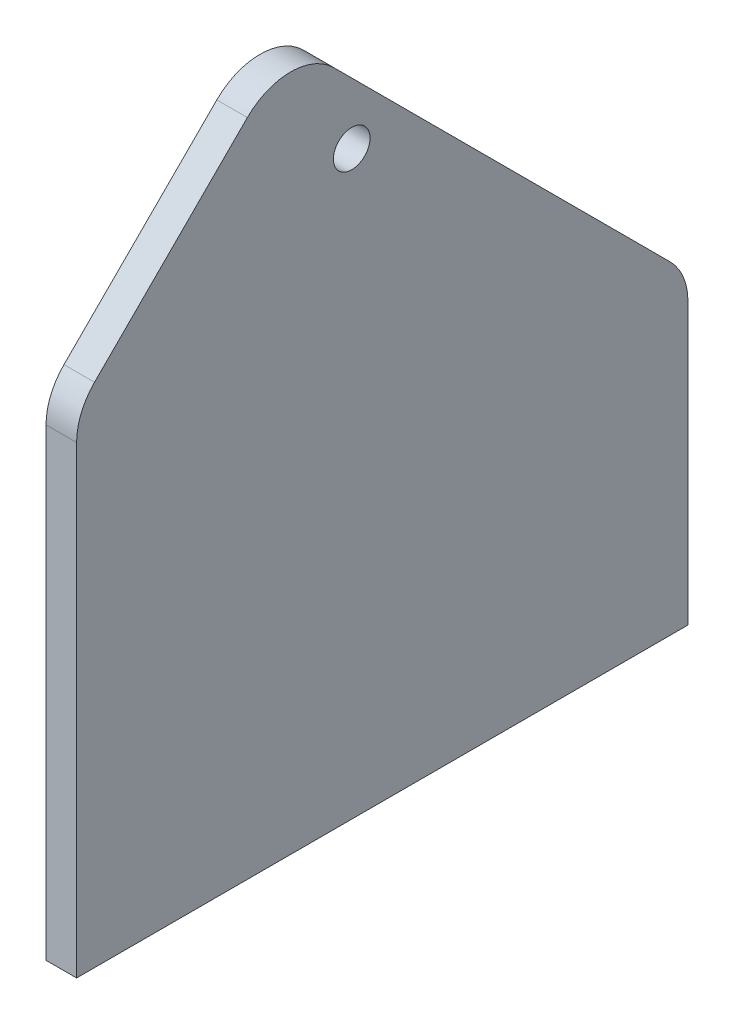
SolidWorks part; units mm, degrees
ref_plane "정면" through (0, 0, 0) normal (0, 0, 1) x (1, 0, 0)
ref_plane "윗면" through (0, 0, 0) normal (0, 1, 0) x (1, 0, 0)
ref_plane "우측면" through (0, 0, 0) normal (1, 0, 0) x (0, 0, -1)
sketch "스케치1" plane through (0, 0, 0) normal (1, 0, 0) x (0, 0, -1)
  line L0 (0, 150) -> (100, 50)
  line L1 (0, 0) -> (100, 0)
  line L2 (0, 0) -> (0, 150)
  line L4 (100, 0) -> (100, 50)
  dimension "D1" = 100
  dimension "D2" = 50
  dimension "D3" = 135
extrude "보스-돌출1" add sketch "스케치1" along normal blind 5
sketch "스케치2" plane through (5, 0, 0) normal (1, 0, 0) x (0, 0, -1)
  line L0 (45, 120) -> (45, 10) construction
  line L3 (0, 0) -> (100, 0) construction
  line L4 (100, 0) -> (100, 50) construction
  circle A0 centre (45, 95) radius 3
  dimension "D1" = 6
  dimension "D2" = 95
  dimension "D3" = 55
extrude "컷-돌출1" cut sketch "스케치2" against normal blind 5
sketch "스케치3" plane through (5, 0, 0) normal (1, 0, 0) x (0, 0, -1)
  line L0 (35, 115) -> (0, 80)
  line L1 (100, 50) -> (0, 150) construction
  line L2 (0, 150) -> (0, 0) construction
  line L3 (0, 80) -> (0, 150)
  line L4 (0, 150) -> (35, 115)
  dimension "D1" = 90
  dimension "D2" = 70
extrude "컷-돌출2" cut sketch "스케치3" against normal blind 10
fillet "필렛2" radius 10 3 edges at (2.5, 50, -100) (2.5, 115, -35) (2.5, 80, 0)
